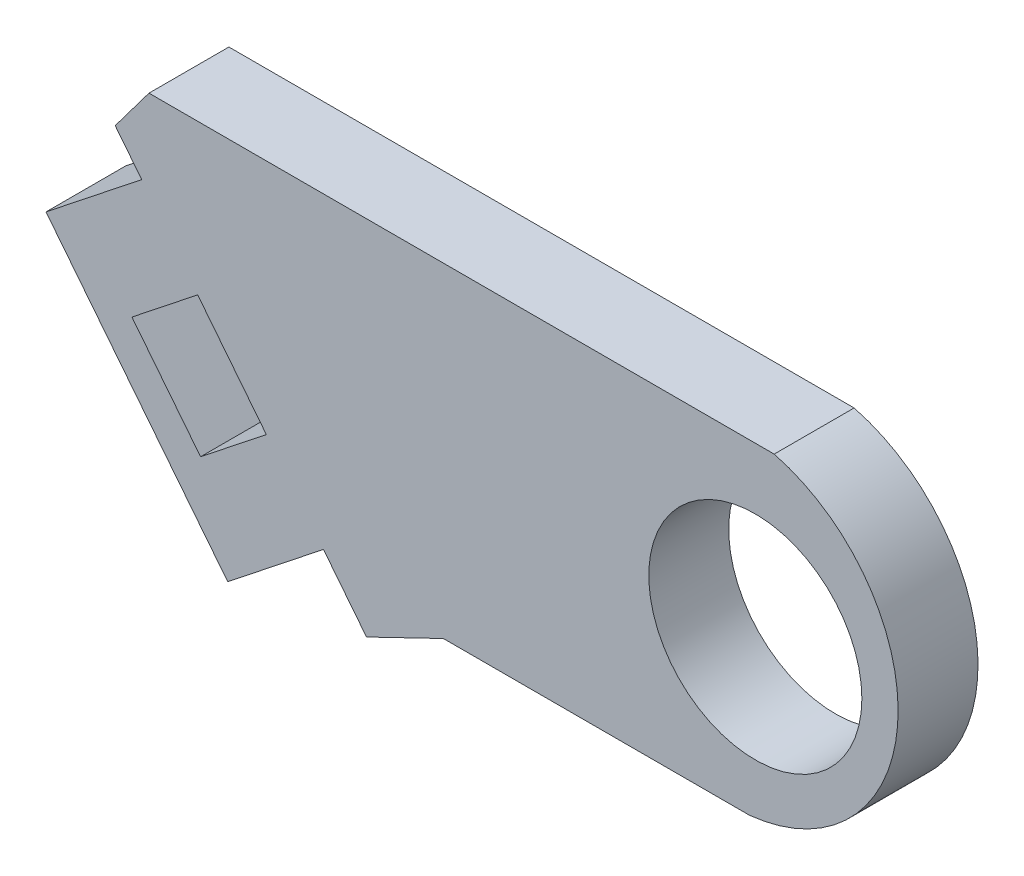
SolidWorks part; units mm, degrees
ref_plane "Front Plane" through (0, 0, 0) normal (0, 0, 1) x (1, 0, 0)
ref_plane "Top Plane" through (0, 0, 0) normal (0, 1, 0) x (1, 0, 0)
ref_plane "Right Plane" through (0, 0, 0) normal (1, 0, 0) x (0, 0, -1)
sketch "Sketch1" plane through (0, 0, 0) normal (0, 0, 1) x (1, 0, 0)
  line L0 (-3.4113, 4.306) -> (3.4113, -4.306)
  line L1 (-32.415, 0) -> (59.8943, 0) construction
  line L2 (8.6213, -3.4988) -> (7.0052, -1.4588)
  line L3 (3.4113, -4.306) -> (7.0052, -1.4588)
  line L4 (-0.1542, 7.533) -> (7.2978, -1.8735) construction
  line L5 (2.2833, 4.4562) -> (4.8604, 1.2032)
  line L6 (2.2833, 4.4562) -> (-0.1857, 2.5001)
  line L7 (4.8604, 1.2032) -> (2.3913, -0.7528)
  line L8 (-0.1857, 2.5001) -> (2.3913, -0.7528)
  line L9 (-3.4113, 4.306) -> (0.1826, 7.1531)
  line L10 (-0.8131, 8.41) -> (0.1826, 7.1531)
  line L11 (-0.8131, 8.41) -> (0.4547, 10.1004)
  line L12 (8.6213, -3.4988) -> (11.5054, -2.1055)
  line L13 (0.4547, 10.1004) -> (23.9257, 10.1004)
  line L14 (11.5054, -2.1055) -> (23.0004, -2.1053)
  line L15 (23.0004, -2.1053) -> (23.2174, 3.8027) construction
  arc A0 (23.0004, -2.1053) -> (23.9257, 10.1004) centre (22.3575, 4.0814) ccw
  circle A1 centre (23.2174, 3.8027) radius 4
  point P4 (0, 0)
  point P22 (0, 0)
  dimension "D19" = 12.44
  dimension "D22" = 8
  dimension "D1" = 51.613
  dimension "D2" = 10.987
  dimension "D3" = 4.585
  dimension "D4" = 90
  dimension "D5" = 4.15
  dimension "D6" = 3.15
  dimension "D7" = 90
  dimension "D8" = 2.096
  dimension "D9" = 90
  dimension "D10" = 1.097
  dimension "D11" = 2.113
  dimension "D12" = 3.4185
  dimension "D13" = 3.203
  dimension "D15" = 23.471
  dimension "D16" = 126.87
  dimension "D17" = 154.217
  dimension "D18" = 11.495
  dimension "D20" = 0.217
  dimension "D21" = 5.908
extrude "Boss-Extrude1" add sketch "Sketch1" against normal blind 3
